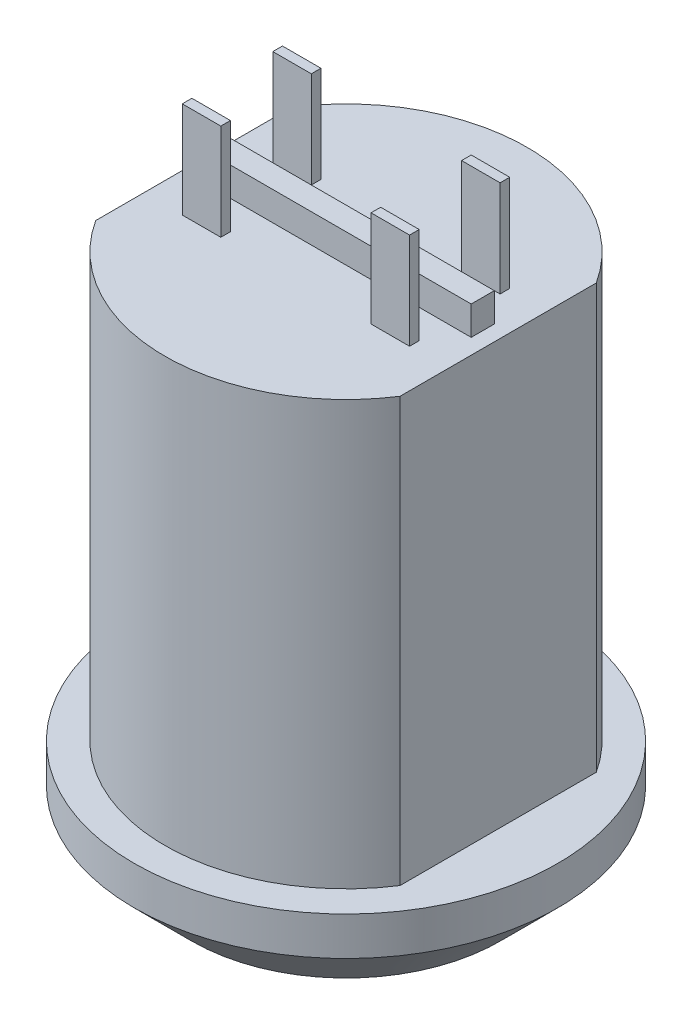
SolidWorks part; units mm, degrees
ref_plane "前视基准面" through (0, 0, 0) normal (0, 0, 1) x (1, 0, 0)
ref_plane "上视基准面" through (0, 0, 0) normal (0, 1, 0) x (1, 0, 0)
ref_plane "右视基准面" through (0, 0, 0) normal (1, 0, 0) x (0, 0, -1)
sketch "草图1" plane through (0, 0, 0) normal (0, 1, 0) x (1, 0, 0)
  circle A0 centre (0, 0) radius 11
  dimension "D1" = 22
extrude "拉伸1" add sketch "草图1" along normal blind 5
chamfer "倒角1" distance 3 angle 45 1 edges at (0, 0, 11)
sketch "草图3" plane through (0, 5, 0) normal (0, 1, 0) x (-1, 0, 0)
  line L0 (-14.0419, 0) -> (17.3595, 0) construction
  line L1 (-7.9, 5.0941) -> (-7.9, -5.0941)
  line L2 (0, 14.0343) -> (0, -15.3362) construction
  line L3 (7.9, 5.0941) -> (7.9, -5.0941)
  arc A0 (-7.9, 5.0941) -> (7.9, 5.0941) centre (0, 0) cw
  arc A1 (-7.9, -5.0941) -> (7.9, -5.0941) centre (0, 0) ccw
  point P9 (-7.9, 0)
  point P13 (7.9, 0)
  dimension "D1" = 15.8
  dimension "D2" = 9.4
extrude "拉伸3" add sketch "草图3" along normal blind 22
sketch "草图4" plane through (0, 0, 0) normal (0, 1, 0) x (-1, 0, 0)
  line L0 (0, -6.2238) -> (0, 5.8769) construction
  line L1 (4.0827, 0) -> (-3.4119, 0) construction
  line L3 (1, -3.75) -> (-1, -3.75)
  line L4 (1, -3.75) -> (1, 3.75)
  line L5 (1, 3.75) -> (-1, 3.75)
  line L6 (-1, -3.75) -> (-1, 3.75)
  dimension "D1" = 2
  dimension "D2" = 7.5
extrude "切除-拉伸1" cut sketch "草图4" along normal blind 10
sketch "草图6" plane through (0, 27, 0) normal (0, 1, 0) x (1, 0, 0)
  line L0 (-15.0728, 0) -> (13.6512, 0) construction
  line L1 (0, 12.0256) -> (0, -12.4335) construction
  line L2 (3.9, 2.6) -> (3.9, 2.1)
  line L3 (-5.9, 2.6) -> (-3.9, 2.6)
  line L4 (-5.9, 2.6) -> (-5.9, 2.1)
  line L5 (-5.9, 2.1) -> (-3.9, 2.1)
  line L6 (-3.9, 2.6) -> (-3.9, 2.1)
  line L7 (5.9, 2.1) -> (3.9, 2.1)
  line L8 (5.9, 2.6) -> (5.9, 2.1)
  line L9 (5.9, 2.6) -> (3.9, 2.6)
  line L10 (5.9, -2.6) -> (3.9, -2.6)
  line L11 (5.9, -2.6) -> (5.9, -2.1)
  line L12 (5.9, -2.1) -> (3.9, -2.1)
  line L13 (-3.9, -2.6) -> (-3.9, -2.1)
  line L14 (-5.9, -2.1) -> (-3.9, -2.1)
  line L15 (-5.9, -2.6) -> (-5.9, -2.1)
  line L16 (-5.9, -2.6) -> (-3.9, -2.6)
  line L17 (3.9, -2.6) -> (3.9, -2.1)
  dimension "D1" = 2
  dimension "D2" = 0.5
  dimension "D3" = 5.2
  dimension "D4" = 11.8
extrude "凸台-拉伸1" add sketch "草图6" along normal blind 5
sketch "草图7" plane through (0, 27, 0) normal (0, 1, 0) x (1, 0, 0)
  line L0 (0, 11.5518) -> (0, -11.9596) construction
  line L1 (-12.4483, 0) -> (14.9999, 0) construction
  line L3 (-7.1, 0.6) -> (7.1, 0.6)
  line L4 (-7.1, 0.6) -> (-7.1, -0.6)
  line L5 (-7.1, -0.6) -> (7.1, -0.6)
  line L6 (7.1, 0.6) -> (7.1, -0.6)
  dimension "D1" = 1.2
  dimension "D3" = 14.2
extrude "凸台-拉伸2" add sketch "草图7" along normal blind 1.5
